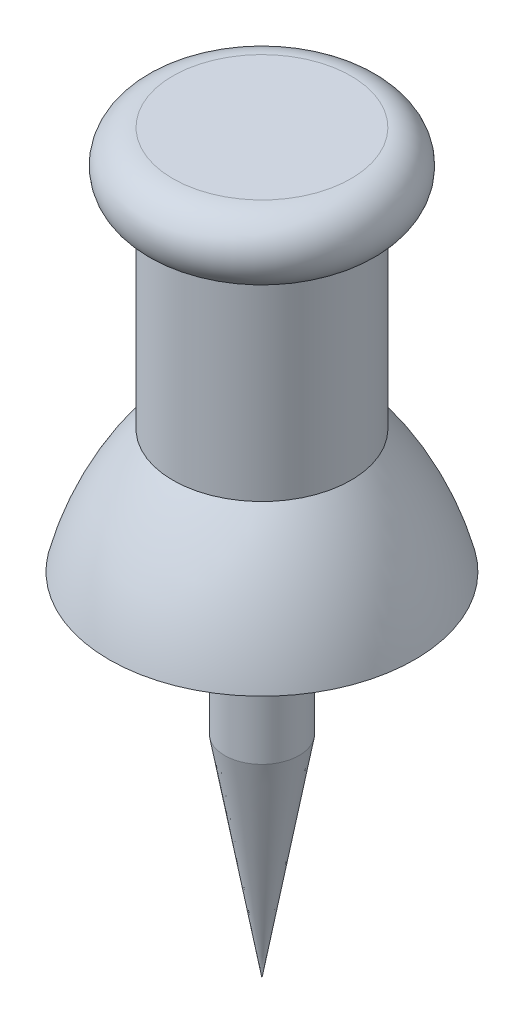
SolidWorks part; units mm, degrees
material "AISI 304"
ref_plane "Front" through (0, 0, 0) normal (0, 0, 1) x (1, 0, 0)
ref_plane "Top" through (0, 0, 0) normal (0, 1, 0) x (1, 0, 0)
ref_plane "Right" through (0, 0, 0) normal (1, 0, 0) x (0, 0, -1)
sketch "Sketch1" plane through (0, 0, 0) normal (0, 0, 1) x (1, 0, 0)
  line L0 (0, 41.7891) -> (0, -37.9901) construction
  line L1 (0, 36.6037) -> (-3.3731, 36.6037)
  line L2 (-3.3731, 34.0995) -> (-3.3731, 26.7143)
  line L3 (-5.7836, 22.0349) -> (-1.4109, 22.0349)
  line L4 (-1.4109, 22.0349) -> (-1.4109, 16.7087)
  line L5 (-1.4109, 16.7087) -> (0, 8.7058)
  line L6 (0, 8.7058) -> (0, 36.6037)
  arc A0 (-3.3731, 36.6037) -> (-3.3731, 34.0995) centre (-3.3731, 35.3516) ccw
  arc A1 (-3.3731, 26.7143) -> (-5.7836, 22.0349) centre (5.4949, 19.1854) ccw
revolve "Revolve1" add sketch "Sketch1" angle 360 about L0
